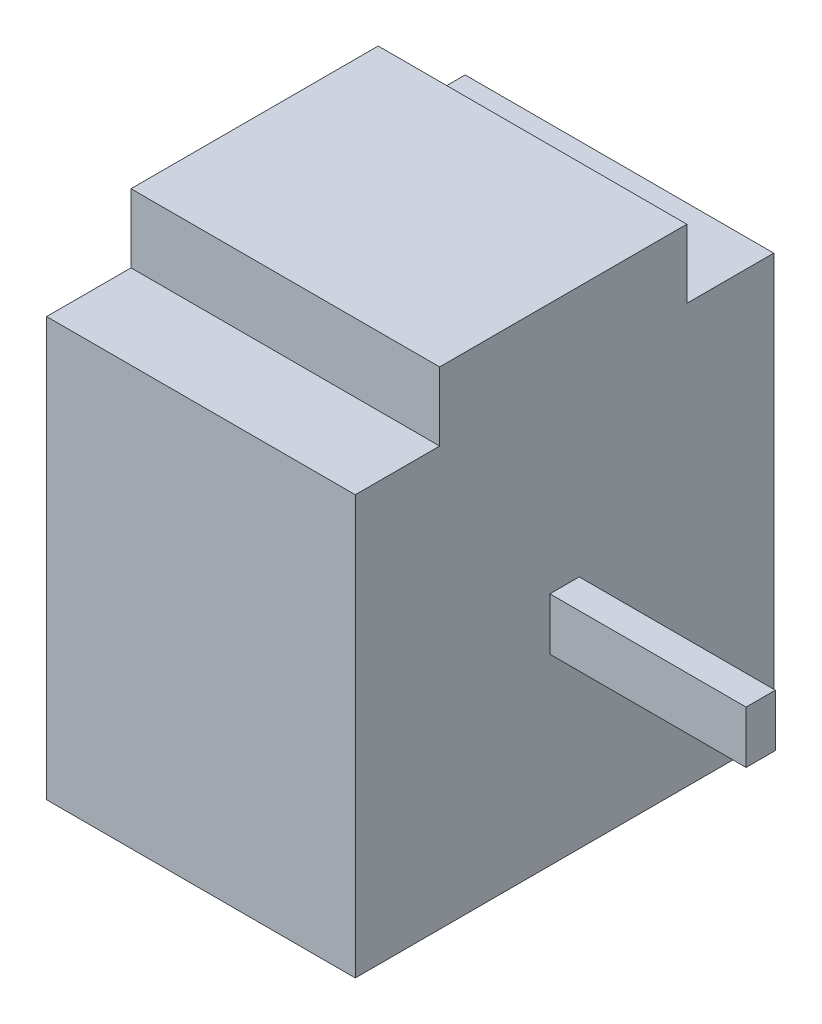
SolidWorks part; units mm, degrees
ref_plane "Front Plane" through (0, 0, 0) normal (0, 0, 1) x (1, 0, 0)
ref_plane "Top Plane" through (0, 0, 0) normal (0, 1, 0) x (1, 0, 0)
ref_plane "Right Plane" through (0, 0, 0) normal (1, 0, 0) x (0, 0, -1)
sketch "Sketch1" plane through (0, 0, 0) normal (1, 0, 0) x (0, 0, -1)
  line L1 (0, 0) -> (16, 0)
  line L2 (0, 0) -> (0, 16)
  line L3 (0, 16) -> (16, 16)
  line L4 (16, 0) -> (16, 16)
  line L5 (3.225, 16) -> (12.675, 16)
  line L6 (3.225, 16) -> (3.225, 18.62)
  line L7 (3.225, 18.62) -> (12.675, 18.62)
  line L8 (12.675, 16) -> (12.675, 18.62)
  dimension "D1" = 16
  dimension "D2" = 16
  dimension "D3" = 9.45
  dimension "D4" = 2.62
  dimension "D6" = 2.62
extrude "Boss-Extrude3" add sketch "Sketch1" along normal blind 11.8 contours L6 L5 L8 L7 | L2 L1 L4 L3
sketch "Sketch2" plane through (11.8, 0, 0) normal (1, 0, 0) x (0, 0, -1)
  line L0 (8, 7) -> (8, 0)
  line L1 (4, 9) -> (12, 9)
  line L2 (4, 9) -> (4, 7)
  line L3 (4, 7) -> (12, 7)
  line L4 (12, 9) -> (12, 7)
  line L5 (0, 0) -> (16, 0) construction
  line L6 (4, 8.3223) -> (0, 8.3223)
  line L7 (0, 0) -> (0, 16) construction
  line L8 (7.44, 7.56) -> (8.56, 7.56)
  line L9 (7.44, 9) -> (8.56, 9)
  line L10 (7.44, 9) -> (7.44, 7)
  line L11 (7.44, 7) -> (8.56, 7)
  line L12 (8.56, 9) -> (8.56, 7)
  line L13 (12, 8.5532) -> (8.56, 8.5532)
  point P4 (12, 8)
  dimension "D1" = 1
  dimension "D2" = 8
  dimension "D3" = 7
  dimension "D4" = 4
  dimension "D5" = 1.12
  dimension "D6" = 3.44
extrude "Boss-Extrude4" add sketch "Sketch2" along normal blind 7.5 contours L12 L8 L10 L3 | L12 L1 L10 L8
